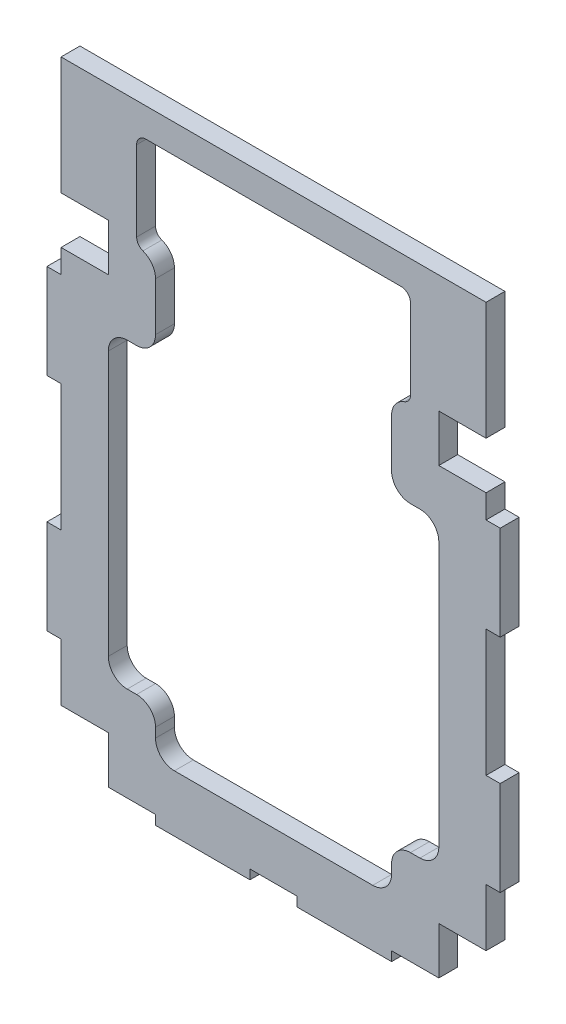
SolidWorks part; units mm, degrees
ref_plane "前视基准面" through (0, 0, 0) normal (0, 0, 1) x (1, 0, 0)
ref_plane "上视基准面" through (0, 0, 0) normal (0, 1, 0) x (1, 0, 0)
ref_plane "右视基准面" through (0, 0, 0) normal (1, 0, 0) x (0, 0, -1)
sketch "Model" plane through (0, 0, 0) normal (0, 0, 1) x (1, 0, 0)
  line L0 (1254.9143, 540.768) -> (1254.9143, 528.2956)
  line L1 (1254.9143, 523.2956) -> (1254.9143, 520.8002)
  line L2 (1254.9143, 510.8002) -> (1254.9143, 497.3785)
  line L3 (1254.9143, 487.3785) -> (1254.9143, 481.2956)
  line L4 (1254.9143, 497.3785) -> (1253.4143, 497.3785)
  line L5 (1254.9143, 487.3785) -> (1253.4143, 487.3785)
  line L6 (1254.9143, 520.8002) -> (1253.4143, 520.8002)
  line L7 (1254.9143, 510.8002) -> (1253.4143, 510.8002)
  line L8 (1254.9143, 481.2956) -> (1259.9143, 481.2956)
  line L9 (1259.9143, 481.2956) -> (1259.9143, 476.2956)
  line L10 (1254.9143, 528.2956) -> (1259.9143, 528.2956)
  line L11 (1259.9143, 528.2956) -> (1259.9143, 523.2956)
  line L12 (1259.9143, 523.2956) -> (1254.9143, 523.2956)
  line L13 (1253.4143, 520.8002) -> (1253.4143, 510.8002)
  line L14 (1253.4143, 497.3785) -> (1253.4143, 487.3785)
  line L15 (1299.9143, 540.768) -> (1254.9143, 540.768)
  line L16 (1279.9143, 476.2956) -> (1274.9143, 476.2956)
  line L17 (1264.9143, 476.2956) -> (1259.9143, 476.2956)
  line L18 (1274.9143, 475.2956) -> (1264.9143, 475.2956)
  line L19 (1264.9143, 476.2956) -> (1264.9143, 475.2956)
  line L20 (1274.9143, 475.2956) -> (1274.9143, 476.2956)
  line L21 (1264.9143, 525.4256) -> (1264.9143, 520.2956)
  line L22 (1262.9143, 518.2956) -> (1261.9143, 518.2956)
  line L23 (1261.9143, 486.2956) -> (1262.9143, 486.2956)
  line L24 (1264.9143, 484.2956) -> (1264.9143, 483.2956)
  line L25 (1263.9143, 537.7163) -> (1290.9143, 537.7163)
  line L26 (1266.9143, 481.2956) -> (1287.9143, 481.2956)
  line L27 (1299.9143, 540.768) -> (1299.9143, 528.2956)
  line L28 (1299.9143, 523.2956) -> (1299.9143, 520.8002)
  line L29 (1299.9143, 510.8002) -> (1299.9143, 497.3785)
  line L30 (1299.9143, 487.3785) -> (1299.9143, 481.2956)
  line L31 (1299.9143, 497.3785) -> (1301.4143, 497.3785)
  line L32 (1299.9143, 487.3785) -> (1301.4143, 487.3785)
  line L33 (1299.9143, 520.8002) -> (1301.4143, 520.8002)
  line L34 (1299.9143, 510.8002) -> (1301.4143, 510.8002)
  line L35 (1299.9143, 481.2956) -> (1294.9143, 481.2956)
  line L36 (1294.9143, 481.2956) -> (1294.9143, 476.2956)
  line L37 (1299.9143, 528.2956) -> (1294.9143, 528.2956)
  line L38 (1294.9143, 528.2956) -> (1294.9143, 523.2956)
  line L39 (1294.9143, 523.2956) -> (1299.9143, 523.2956)
  line L40 (1301.4143, 520.8002) -> (1301.4143, 510.8002)
  line L41 (1301.4143, 497.3785) -> (1301.4143, 487.3785)
  line L42 (1289.9143, 476.2956) -> (1294.9143, 476.2956)
  line L43 (1279.9143, 475.2956) -> (1289.9143, 475.2956)
  line L44 (1289.9143, 476.2956) -> (1289.9143, 475.2956)
  line L45 (1279.9143, 475.2956) -> (1279.9143, 476.2956)
  line L46 (1291.9143, 518.2956) -> (1292.9143, 518.2956)
  line L47 (1292.9143, 486.2956) -> (1291.9143, 486.2956)
  line L48 (1294.9143, 516.2956) -> (1294.9143, 488.2956)
  line L49 (1259.9143, 516.2956) -> (1259.9143, 488.2956)
  line L50 (1262.9143, 528.254) -> (1262.9143, 536.7163)
  line L51 (1291.9143, 528.254) -> (1291.9143, 536.7163)
  line L52 (1289.9143, 525.4256) -> (1289.9143, 520.2956)
  line L53 (1289.9143, 484.2956) -> (1289.9143, 483.2956)
  arc A0 (1261.9143, 518.2956) -> (1259.9143, 516.2956) centre (1261.9143, 516.2956) ccw
  arc A1 (1264.9143, 525.4256) -> (1263.581, 527.3112) centre (1262.9143, 525.4256) ccw
  arc A2 (1262.9143, 528.254) -> (1263.581, 527.3112) centre (1263.9143, 528.254) ccw
  arc A3 (1262.9143, 518.2956) -> (1264.9143, 520.2956) centre (1262.9143, 520.2956) ccw
  arc A4 (1259.9143, 488.2956) -> (1261.9143, 486.2956) centre (1261.9143, 488.2956) ccw
  arc A5 (1264.9143, 483.2956) -> (1266.9143, 481.2956) centre (1266.9143, 483.2956) ccw
  arc A6 (1264.9143, 484.2956) -> (1262.9143, 486.2956) centre (1262.9143, 484.2956) ccw
  arc A7 (1294.9143, 516.2956) -> (1292.9143, 518.2956) centre (1292.9143, 516.2956) ccw
  arc A8 (1291.2477, 527.3112) -> (1289.9143, 525.4256) centre (1291.9143, 525.4256) ccw
  arc A9 (1291.2477, 527.3112) -> (1291.9143, 528.254) centre (1290.9143, 528.254) ccw
  arc A10 (1289.9143, 520.2956) -> (1291.9143, 518.2956) centre (1291.9143, 520.2956) ccw
  arc A11 (1292.9143, 486.2956) -> (1294.9143, 488.2956) centre (1292.9143, 488.2956) ccw
  arc A12 (1287.9143, 481.2956) -> (1289.9143, 483.2956) centre (1287.9143, 483.2956) ccw
  arc A13 (1291.9143, 486.2956) -> (1289.9143, 484.2956) centre (1291.9143, 484.2956) ccw
  arc A14 (1263.9143, 537.7163) -> (1262.9143, 536.7163) centre (1263.9143, 536.7163) ccw
  arc A15 (1291.9143, 536.7163) -> (1290.9143, 537.7163) centre (1290.9143, 536.7163) ccw
extrude "凸台-拉伸1" add sketch "Model" along normal blind 2
